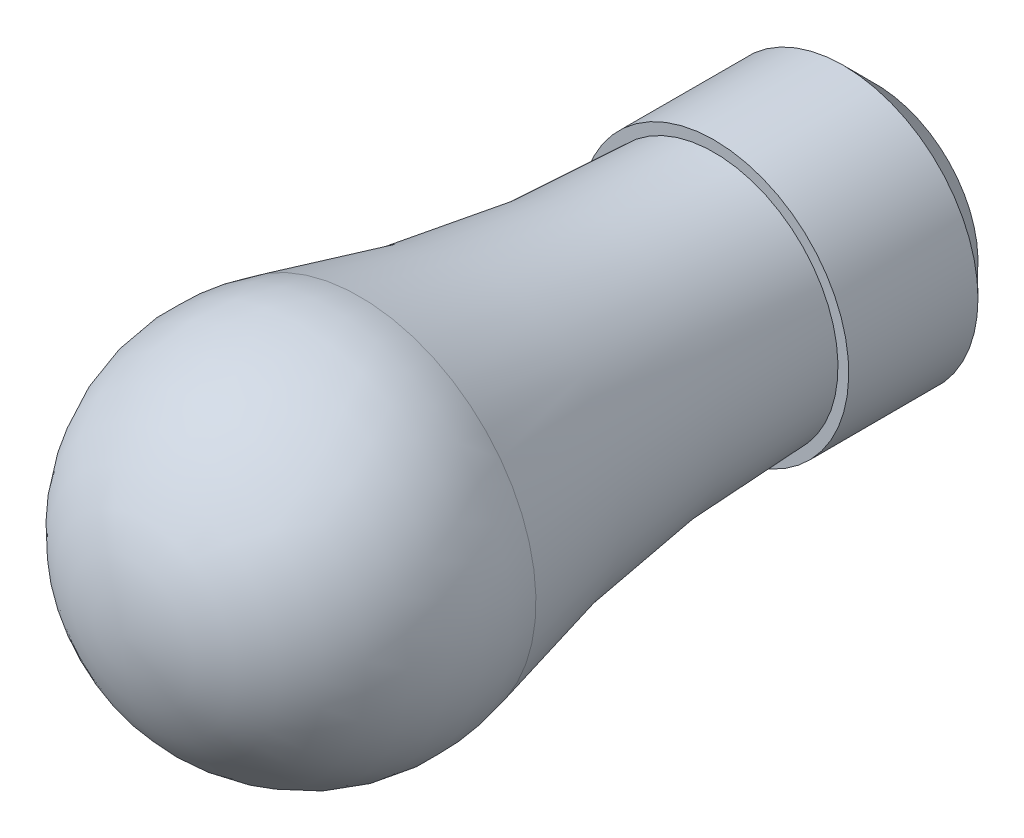
SolidWorks part; units mm, degrees
ref_plane "Front Plane" through (0, 0, 0) normal (0, 0, 1) x (1, 0, 0)
ref_plane "Top Plane" through (0, 0, 0) normal (0, 1, 0) x (1, 0, 0)
ref_plane "Right Plane" through (0, 0, 0) normal (1, 0, 0) x (0, 0, -1)
sketch "Sketch1" plane through (0, 0, 0) normal (1, 0, 0) x (0, 0, -1)
  line L0 (0, 0) -> (-33.5777, 0) construction
  line L1 (0, 0) -> (-15, 0)
  line L2 (0, 0) -> (0, -12.5)
  line L3 (0, -12.5) -> (-15, -12.5)
  line L4 (-15, 0) -> (-15, -12.5)
  dimension "D1" = 12.5
  dimension "D2" = 15
revolve "Revolve1" add sketch "Sketch1" angle 360 about L0
chamfer "Chamfer1" distance 3 angle 45 1 edges at (0, 12.5, 0)
sketch "Sketch2" plane through (0, 0, 0) normal (1, 0, 0) x (0, 0, -1)
  line L0 (0, 0) -> (-70, 0) construction
  line L1 (-15, 0) -> (-15, -11.5)
  line L2 (-15, 12.5) -> (-15, -12.5) construction
  line L3 (-70, 4.1251) -> (-70, -33.1922) construction
  line L4 (-15, -12.5) -> (-3, -12.5) construction
  line L5 (-70, 0) -> (-15, 0)
  arc A0 (-15, -11.5) -> (-47.9235, -16.3784) centre (-15, -125.0359) ccw
  arc A1 (-47.9235, -16.3784) -> (-70, 0) centre (-52.8862, 0) cw
  dimension "D2" = 1
  dimension "D3" = 113.5359
  dimension "D1" = 70
revolve "Revolve2" add sketch "Sketch2" angle 360 about L5
